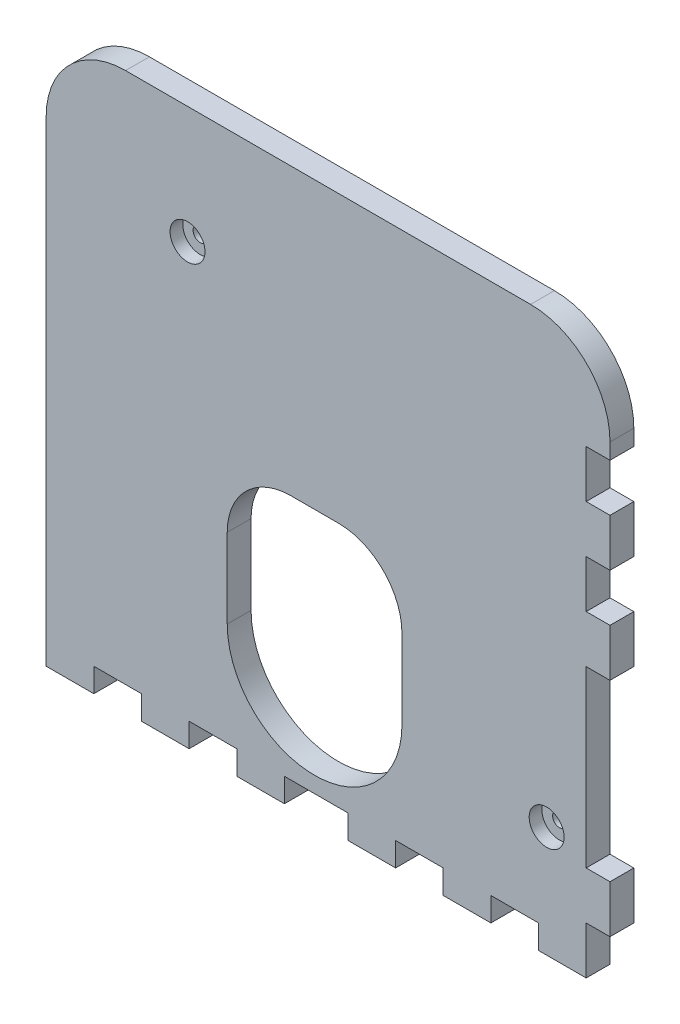
SolidWorks part; units mm, degrees
ref_plane "Front Plane" through (0, 0, 0) normal (0, 0, 1) x (1, 0, 0)
ref_plane "Top Plane" through (0, 0, 0) normal (0, 1, 0) x (1, 0, 0)
ref_plane "Right Plane" through (0, 0, 0) normal (1, 0, 0) x (0, 0, -1)
sketch "Sketch1" plane through (0, 0, 0) normal (0, 0, 1) x (1, 0, 0)
  line L0 (-120, 170) -> (135, 170)
  line L1 (170, 110) -> (170, 80)
  line L2 (-170, -170) -> (-170, 120)
  line L3 (170, 50) -> (170, 20)
  line L4 (-55.9954, -49.8) -> (-55.9954, -99.8)
  line L5 (54.0046, -99.8) -> (54.0046, -49.8)
  line L6 (14.0046, -9.8) -> (-15.9954, -9.8)
  line L8 (170, 170) -> (185, 170)
  line L9 (170, 80) -> (185, 80)
  line L10 (-170, -170) -> (-170, -179.8)
  line L11 (-170, -179.8) -> (-140, -179.8)
  line L12 (-140, -179.8) -> (-140, -164.8)
  line L13 (-140, -164.8) -> (-110, -164.8)
  line L14 (-110, -164.8) -> (-110, -179.8)
  line L15 (-110, -179.8) -> (-80, -179.8)
  line L16 (-80, -179.8) -> (-80, -164.8)
  line L17 (-80, -164.8) -> (-50, -164.8)
  line L18 (-50, -164.8) -> (-50, -179.8)
  line L19 (-50, -179.8) -> (-20, -179.8)
  line L20 (-20, -179.8) -> (-20, -164.8)
  line L21 (-20, -164.8) -> (20, -164.8)
  line L22 (20, -164.8) -> (20, -179.8)
  line L23 (20, -179.8) -> (50, -179.8)
  line L24 (50, -179.8) -> (50, -164.8)
  line L25 (50, -164.8) -> (80, -164.8)
  line L26 (80, -164.8) -> (80, -179.8)
  line L27 (80, -179.8) -> (110, -179.8)
  line L28 (110, -179.8) -> (110, -164.8)
  line L29 (110, -164.8) -> (140, -164.8)
  line L30 (140, -164.8) -> (140, -179.8)
  line L31 (140, -179.8) -> (170, -179.8)
  line L32 (170, 110) -> (185, 110)
  line L33 (80, -164.8) -> (80, -179.8879) construction
  line L34 (185, 120) -> (185, 110)
  line L35 (170, -10) -> (170, -119.8)
  line L36 (170, 50) -> (185, 50)
  line L37 (185, 80) -> (185, 50)
  line L38 (170, 110) -> (170, 80)
  line L39 (170, 50) -> (170, 20)
  line L40 (170, 20) -> (185, 20)
  line L41 (170, -149.8) -> (170, -179.8)
  line L42 (170, -10) -> (185, -10)
  line L43 (185, 20) -> (185, -10)
  line L44 (170, -10) -> (170, -119.8)
  line L45 (170, -149.8) -> (185, -149.8)
  line L47 (170, -119.8) -> (185, -119.8)
  line L48 (185, -149.8) -> (185, -119.8)
  line L49 (170, -149.8) -> (170, -179.8)
  line L61 (-80, -179.7399) -> (-80, -164.8) construction
  circle A0 centre (145.1048, -110) radius 11
  arc A1 (-15.9954, -9.8) -> (-55.9954, -49.8) centre (-15.9954, -49.8) ccw
  arc A2 (-55.9954, -99.8) -> (54.0046, -99.8) centre (-0.9954, -99.8) ccw
  arc A3 (54.0046, -49.8) -> (14.0046, -9.8) centre (14.0046, -49.8) ccw
  arc A4 (-170, 120) -> (-120, 170) centre (-120, 120) cw
  circle A5 centre (-81, 96.1443) radius 11
  arc A6 (185, 120) -> (135, 170) centre (135, 120) ccw
  point P0 (0, 0)
  dimension "D5" = 22
  dimension "D28" = 50
  dimension "D29" = 22
  dimension "D12" = 50
  dimension "D3" = 340
  dimension "D4" = 15
  dimension "D6" = 349.8
  dimension "D7" = 30
  dimension "D8" = 30
  dimension "D9" = 30
  dimension "D10" = 30
  dimension "D11" = 30
  dimension "D13" = 15
  dimension "D14" = 30
  dimension "D15" = 30
  dimension "D16" = 30
  dimension "D17" = 15
  dimension "D18" = 15
  dimension "D19" = 30
  dimension "D20" = 30
  dimension "D21" = 30
  dimension "D22" = 30
  dimension "D23" = 30
  dimension "D24" = 40
  dimension "D25" = 30
extrude "Boss-Extrude1" add sketch "Sketch1" along normal blind 15
sketch "Sketch2" [suppressed] plane through (0, 0, 0) normal (0, 0, 1) x (1, 0, 0)
  circle A0 centre (145.1048, -110) radius 11
  circle A1 centre (145.1048, -110) radius 4.25
  dimension "D1" = 8.5
extrude "Boss-Extrude2" [suppressed] add sketch "Sketch2" along normal blind 10
sketch "Sketch3" [suppressed] plane through (0, 0, 0) normal (0, 0, 1) x (1, 0, 0)
  circle A0 centre (-81, 96.1443) radius 11
  circle A1 centre (-81, 96.1443) radius 4.25
  dimension "D1" = 8.5
extrude "Boss-Extrude3" [suppressed] add sketch "Sketch3" along normal blind 10
sketch "Sketch4" plane through (0, 0, 0) normal (0, 0, -1) x (-1, 0, 0)
  circle A0 centre (81, 96.1443) radius 11
  circle A1 centre (81, 96.1443) radius 4.5
extrude "Boss-Extrude4" add sketch "Sketch4" against normal blind 7 separate body
sketch "Sketch5" plane through (0, 0, 0) normal (0, 0, -1) x (-1, 0, 0)
  circle A0 centre (-145.1048, -110) radius 11
  circle A1 centre (-145.1048, -110) radius 4.25
extrude "Boss-Extrude5" add sketch "Sketch5" against normal blind 7
